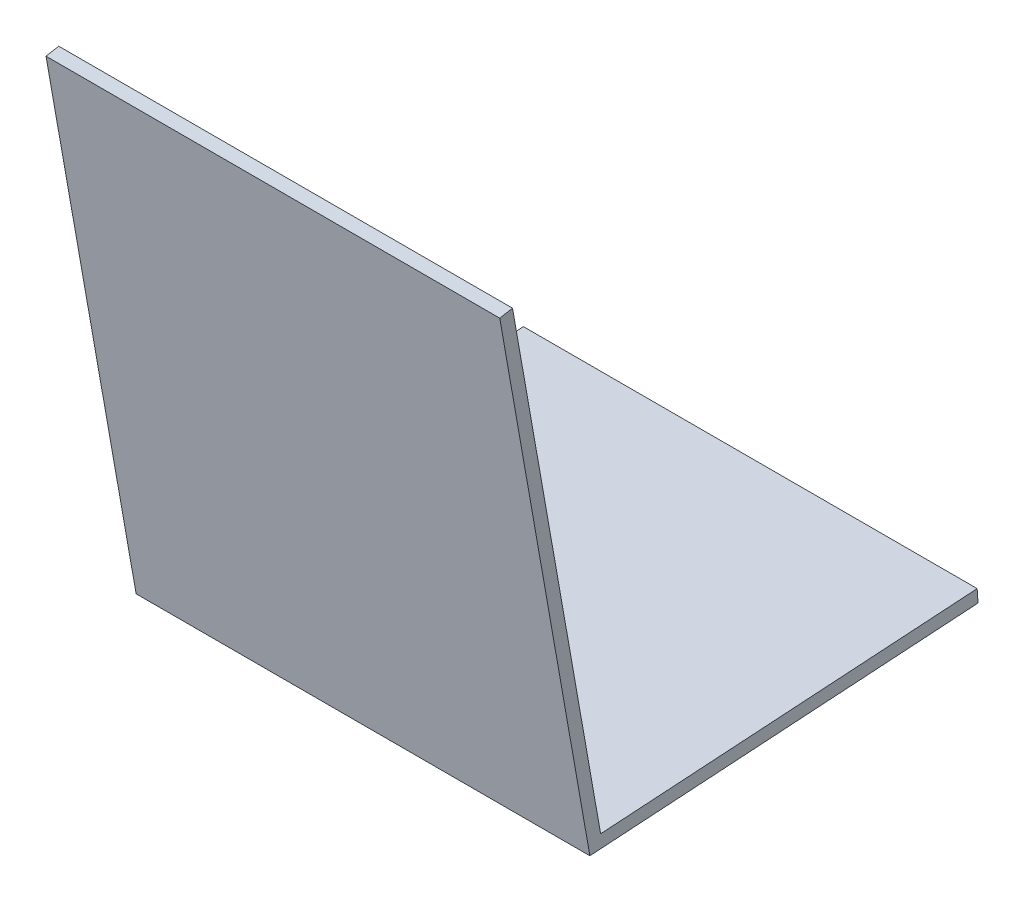
SolidWorks part; units mm, degrees
ref_plane "Front Plane" through (0, 0, 0) normal (0, 0, 1) x (1, 0, 0)
ref_plane "Top Plane" through (0, 0, 0) normal (0, 1, 0) x (1, 0, 0)
ref_plane "Right Plane" through (0, 0, 0) normal (1, 0, 0) x (0, 0, -1)
sketch "Sketch1" plane through (0, 0, 0) normal (1, 0, 0) x (0, 0, -1)
  line L0 (-923.9121, 406.6134) -> (-854.398, 12.7)
  line L1 (-854.398, 12.7) -> (-555.0091, 31.839)
  line L2 (-914.0643, 408.3513) -> (-846.1053, 23.2505)
  line L3 (-846.1053, 23.2505) -> (-555.6471, 41.8186)
  line L4 (-923.9121, 406.6134) -> (-914.0643, 408.3513)
  line L5 (-555.0091, 31.839) -> (-555.6471, 41.8186)
  line L6 (-837.3, 12.7) -> (-862.7, 12.7) construction
  point P6 (0, 0)
  dimension "D1" = 10
  dimension "D2" = 400
  dimension "D3" = 300
extrude "Boss-Extrude1" add sketch "Sketch1" along normal mid plane 350
